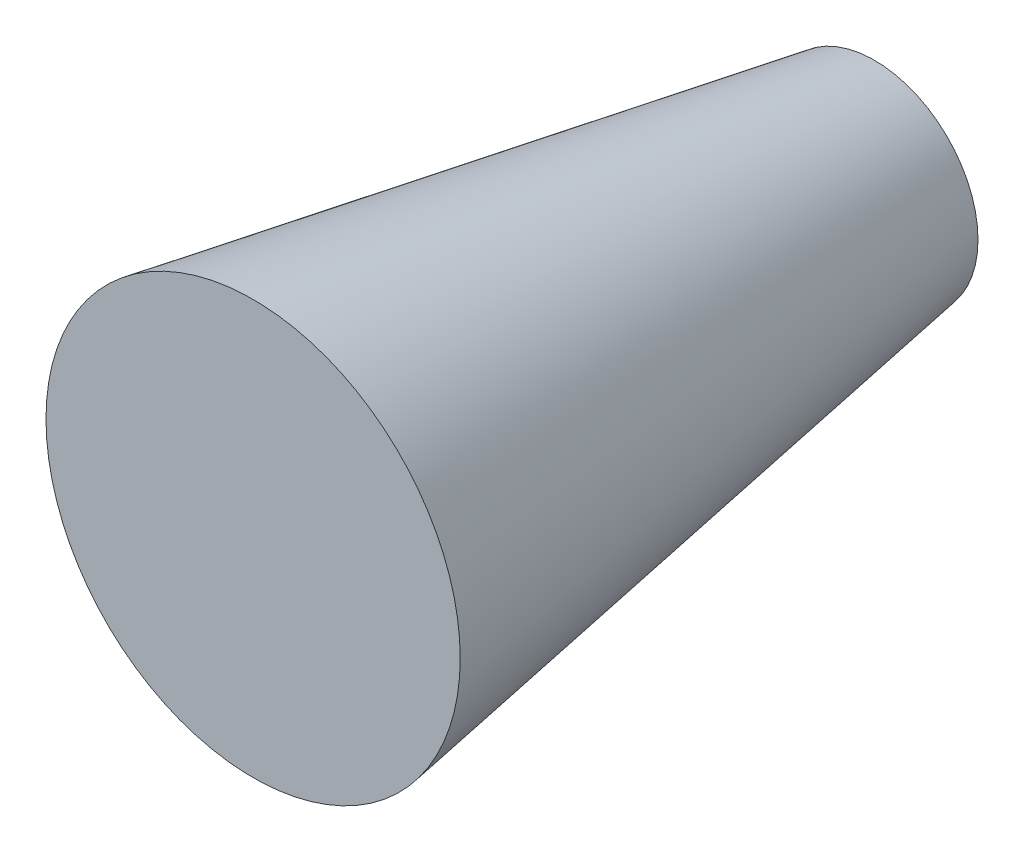
SolidWorks part; units mm, degrees
ref_plane "前视基准面" through (0, 0, 0) normal (0, 0, 1) x (1, 0, 0)
ref_plane "上视基准面" through (0, 0, 0) normal (0, 1, 0) x (1, 0, 0)
ref_plane "右视基准面" through (0, 0, 0) normal (1, 0, 0) x (0, 0, -1)
other "Configuration Table"
sketch "Profile1" plane through (0, 0, 0) normal (0, 0, 1) x (1, 0, 0)
  circle A0 centre (0, 0) radius 5
ref_plane "Plane1" through (0, 0, 30) normal (0, 0, 1) x (1, 0, 0)
sketch "Profile2" plane through (0, 0, 30) normal (0, 0, 1) x (1, 0, 0)
  circle A0 centre (0, 0) radius 10
loft "loft_circle10_20" add profiles "Profile1", "Profile2"
